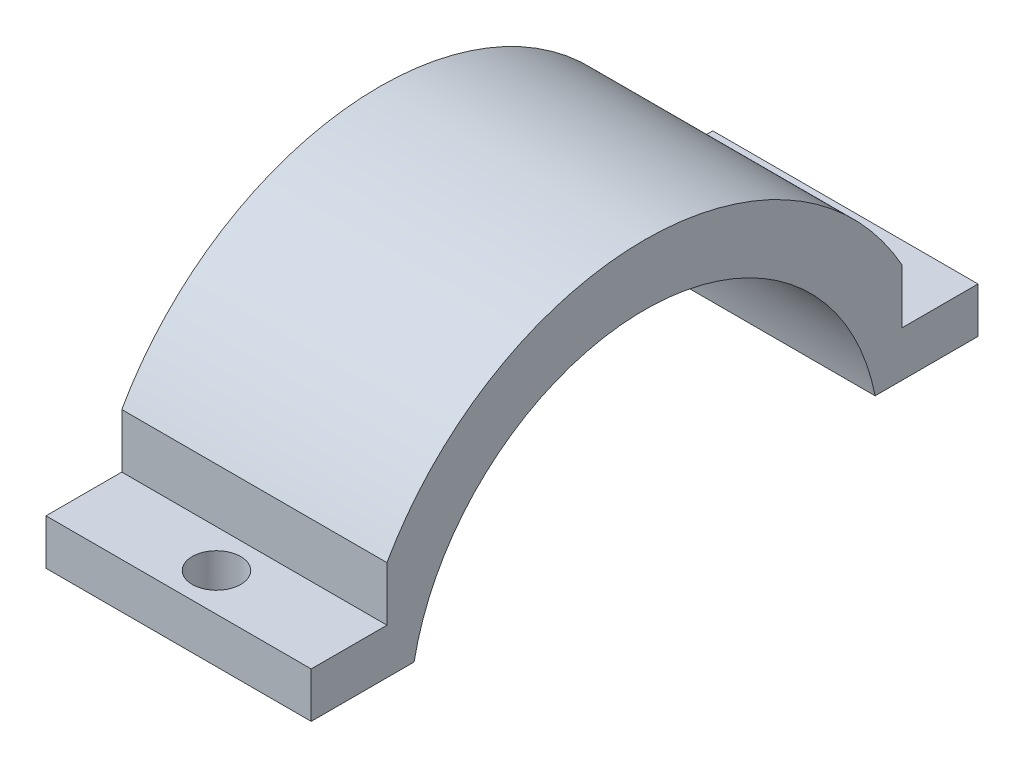
SolidWorks part; units mm, degrees
ref_plane "前视基准面" through (0, 0, 0) normal (0, 0, 1) x (1, 0, 0)
ref_plane "上视基准面" through (0, 0, 0) normal (0, 1, 0) x (1, 0, 0)
ref_plane "右视基准面" through (0, 0, 0) normal (1, 0, 0) x (0, 0, -1)
sketch "草图1" plane through (0, 0, 0) normal (0, 1, 0) x (1, 0, 0)
  line L1 (0, 0) -> (17, 0)
  line L2 (0, 0) -> (0, -40)
  line L3 (0, -40) -> (17, -40)
  line L4 (17, 0) -> (17, -40)
  dimension "D1" = 17
  dimension "D2" = 40
extrude "凸台-拉伸1" add sketch "草图1" along normal blind 50
sketch "草图2" plane through (0, 0, 0) normal (0, -1, 0) x (1, 0, 0)
  line L0 (0, 39) -> (0, 40)
  line L1 (-0.5, 39) -> (17, 39) construction
  line L2 (0, 0) -> (0, 40) construction
  line L3 (0, 40) -> (17, 40)
  line L4 (17, 40) -> (17, 39)
  line L5 (17, 40) -> (17, 0) construction
  line L6 (17, 39) -> (0, 39)
extrude "切除-拉伸1" cut sketch "草图2" against normal through all
sketch "草图4" plane through (0, 0, 0) normal (0, -1, 0) x (1, 0, 0)
  line L2 (-0.5, 0) -> (0, 0)
  line L3 (0, 0) -> (0, 39)
  line L4 (-0.5, 0) -> (-0.5, 39)
  line L5 (-0.5, 39) -> (0, 39)
extrude "凸台-拉伸2" add sketch "草图4" against normal up to vertex (50 mm away) up to point (0, 50, 39)
sketch "草图5" plane through (17, 0, 0) normal (1, 0, 0) x (0, 0, -1)
  circle A0 centre (-22, 4.5) radius 15.5
extrude "切除-拉伸2" cut sketch "草图5" against normal up to vertex (17.5 mm away)
sketch "草图6" plane through (17, 0, 0) normal (1, 0, 0) x (0, 0, -1)
  line L0 (0, 24) -> (0, 3)
  line L2 (-22, 24) -> (-5, 24)
  line L3 (0, 50) -> (0, 0) construction
  line L4 (0, 24) -> (0, 50)
  line L5 (0, 50) -> (-39, 50)
  line L6 (-39, 50) -> (-39, 24)
  line L7 (-39, 50) -> (-39, 0) construction
  line L8 (-39, 24) -> (-22, 24)
  line L9 (0, 0) -> (0, 3)
  line L10 (0, 3) -> (-5, 3)
  line L11 (-5, 3) -> (-5, 24)
  line L12 (0, 24) -> (0, 3)
  line M11 (0, 0) -> (0, 50)
  line M12 (0, 50) -> (-39, 50)
  line M13 (-39, 50) -> (-39, 0)
extrude "切除-拉伸3" cut sketch "草图6" against normal up to vertex (17.5 mm away) contours L11 L10 L8 L2 M11 M12 M13
sketch "草图7" plane through (0, 3, 0) normal (0, 1, 0) x (1, 0, 0)
  line L0 (8.25, -5) -> (8.25, 0)
  line L1 (-0.5, -5) -> (17, -5) construction
  line L2 (-0.5, 0) -> (17, 0) construction
  circle A0 centre (8.25, -2.5) radius 1.6
extrude "切除-拉伸4" cut sketch "草图7" against normal up to vertex (3 mm away) contours L0 A0 | L0 A0
sketch "草图8" plane through (-0.5, 0, 0) normal (-1, 0, 0) x (0, 0, 1)
  line L0 (22, 4.5) -> (5, 4.5)
  line L1 (5, 3) -> (5, 24) construction
  line L2 (22, 4.5) -> (39, 4.5)
  line L3 (39, 24) -> (39, 0) construction
  line L4 (39, 4.5) -> (39, 0)
  line L5 (39, 0) -> (17.2565, -28.4468)
  line L6 (17.2565, -28.4468) -> (-8.6135, 4.5)
  line L7 (-8.6135, 4.5) -> (5, 4.5)
  circle A0 centre (22, 4.5) radius 15.5
  line M2 (5, 24) -> (5, 3)
  line M3 (5, 3) -> (0, 3)
  line M4 (0, 3) -> (0, 0)
  line M5 (0, 0) -> (7.1676, 0)
  arc M6 (7.1676, 0) -> (36.8324, 0) centre (22, 4.5) cw
  line M7 (36.8324, 0) -> (39, 0)
  line M8 (39, 0) -> (39, 24)
extrude "切除-拉伸7" cut sketch "草图8" against normal blind 64 contours A0 L7 L6 L5 M5 M4 M3 M2 M7 | L0 M6 M2 M3 M4 M5 | A0 L2 L0 M6 | L2 M6 M7 M8
sketch "草图9" plane through (-0.5, 0, 0) normal (-1, 0, 0) x (0, 0, 1)
  line L12 (39, 7.4784) -> (44, 7.4784)
  line L13 (5, 4.5) -> (5, 24) construction
  line L14 (39, 24) -> (39, 4.5) construction
  line L15 (44, 7.4784) -> (44, 10.4784)
  line L16 (44, 10.4784) -> (39, 10.4784)
  line L17 (39, 10.4784) -> (39, 7.4784)
  line L18 (5, 7.4784) -> (0, 7.4784)
  line L19 (0, 7.4784) -> (0, 10.4784)
  line L20 (0, 10.4784) -> (5, 10.4784)
  line L21 (5, 10.4784) -> (5, 7.4784)
  dimension "D1" = 3
  dimension "D2" = 3
  dimension "D3" = 5
extrude "凸台-拉伸3" add sketch "草图9" against normal up to vertex (17.5 mm away)
sketch "草图10" plane through (-0.5, 0, 0) normal (-1, 0, 0) x (0, 0, 1)
  line L0 (6.5, 4.5) -> (37.5, 4.5)
  line L1 (5, 14.0525) -> (5, 24)
  line L2 (5, 10.4784) -> (5, 24) construction
  line L3 (5, 24) -> (39, 24)
  line L4 (39, 24) -> (39, 14.0525)
  line L5 (39, 24) -> (39, 10.4784) construction
  arc A0 (39, 14.0525) -> (5, 14.0525) centre (22, 4.5) ccw
  line M1 (5, 24) -> (5, 10.4784)
  line M9 (39, 10.4784) -> (39, 24)
  line M10 (39, 24) -> (5, 24)
extrude "切除-拉伸8" cut sketch "草图10" against normal through all and the other way through all contours A0 L3 M1 | A0 M9 M10
sketch "草图12" plane through (0, 10.4784, 0) normal (0, 1, 0) x (1, 0, 0)
  line L0 (8.25, -39) -> (8.25, -44)
  line L1 (17, -39) -> (-0.5, -39) construction
  line L2 (17, -44) -> (-0.5, -44) construction
  line L3 (8.25, 0) -> (8.25, -5)
  line L4 (17, 0) -> (-0.5, 0) construction
  line L5 (17, -5) -> (-0.5, -5) construction
  circle A0 centre (8.25, -41.5) radius 1.6
  circle A1 centre (8.25, -2.5) radius 1.6
  dimension "D1" = 3.2
  dimension "D2" = 3.2
extrude "切除-拉伸10" cut sketch "草图12" against normal up to next contours L0 A0 | L0 A0 | L3 A1 | L3 A1
sketch "草图13" plane through (17, 0, 0) normal (1, 0, 0) x (0, 0, -1)
  line L0 (-39, 7.4784) -> (-37.2111, 7.4784)
  line L1 (-37.2111, 7.4784) -> (-37.5, 4.5)
  line L2 (-37.5, 4.5) -> (-39, 4.5)
  line L3 (-39, 4.5) -> (-39, 7.4784)
  line L4 (-5, 7.4784) -> (-6.7889, 7.4784)
  line L5 (-6.7889, 7.4784) -> (-6.5, 4.5)
  line L6 (-6.5, 4.5) -> (-5, 4.5)
  line L7 (-5, 4.5) -> (-5, 7.4784)
  arc A0 (-6.5, 4.5) -> (-37.5, 4.5) centre (-22, 4.5) ccw construction
extrude "切除-拉伸11" cut sketch "草图13" against normal up to next
